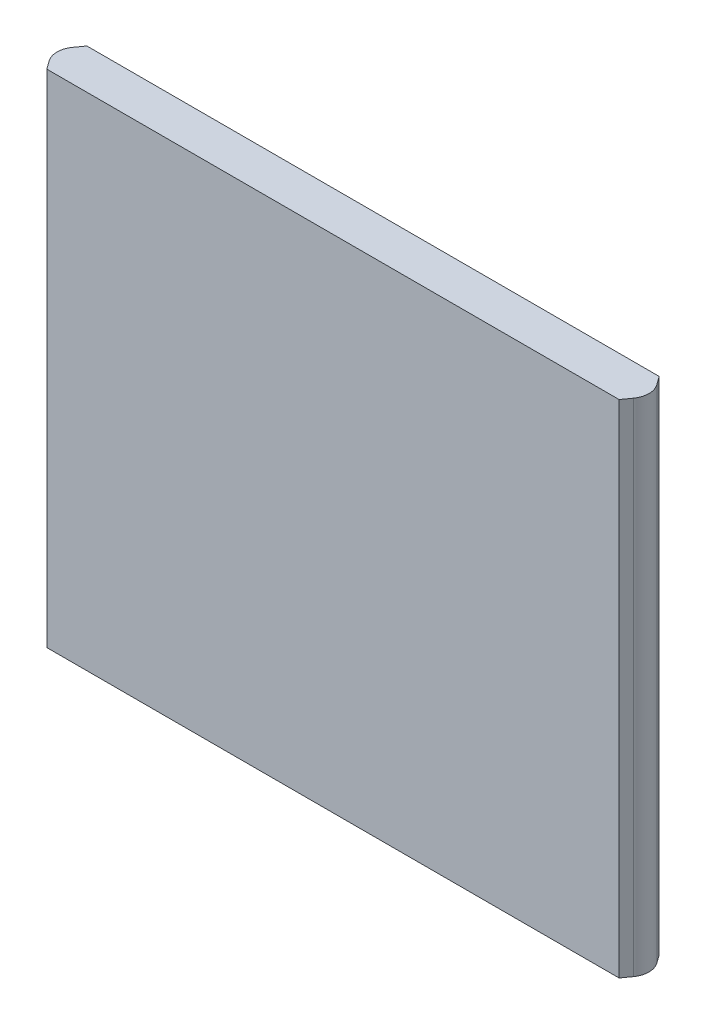
SolidWorks part; units mm, degrees
ref_plane "Front" through (0, 0, 0) normal (0, 0, 1) x (1, 0, 0)
ref_plane "Top" through (0, 0, 0) normal (0, 1, 0) x (1, 0, 0)
ref_plane "Right" through (0, 0, 0) normal (1, 0, 0) x (0, 0, -1)
sketch "草图1" plane through (0, 0, 0) normal (0, 0, 1) x (1, 0, 0)
  line L0 (0, 0) -> (0, -25)
  line L1 (0, -25) -> (30, -25)
  line L2 (30, -25) -> (30, 0)
  line L3 (30, 0) -> (0, 0)
extrude "凸台-拉伸1" add sketch "草图1" along normal blind 2
sketch "草图2" plane through (0, -25, 0) normal (0, -1, 0) x (1, 0, 0)
  line L0 (0.4228, 1.5855) -> (0.7222, 2)
  line L1 (0, 2) -> (0, 0) construction
  line L2 (0, 2) -> (30, 2) construction
  line L3 (0.4228, 0.4145) -> (0.7222, 0)
  line L4 (0, 0) -> (30, 0) construction
  line L5 (0.7222, 0) -> (0, 0)
  line L6 (0, 0) -> (0, 1)
  line L7 (0, 2) -> (0, 1)
  line L8 (0, 2) -> (0.7222, 2)
  line L9 (15, 2) -> (15, -4.0308) construction
  line L10 (30, 0) -> (30, 1)
  line L11 (29.2778, 0) -> (30, 0)
  line L12 (29.5772, 0.4145) -> (29.2778, 0)
  line L13 (29.5772, 1.5855) -> (29.2778, 2)
  line L14 (30, 2) -> (29.2778, 2)
  line L15 (30, 2) -> (30, 1)
  arc A0 (0.4228, 0.4145) -> (0.4228, 1.5855) centre (1.2335, 1) cw
  arc A1 (29.5772, 0.4145) -> (29.5772, 1.5855) centre (28.7665, 1) ccw
  dimension "D1" = 1
extrude "切除-拉伸1" cut sketch "草图2" against normal through all
sketch "草图3" plane through (0, -25, 0) normal (0, -1, 0) x (1, 0, 0)
  line L0 (15, 2) -> (15, 0)
  line L1 (0.7222, 2) -> (29.2778, 2) construction
  line L2 (0.7222, 0) -> (29.2778, 0) construction
  circle A0 centre (15, 1) radius 0.3
extrude "切除-拉伸2" cut sketch "草图3" against normal blind 3 contours L0 A0 | L0 A0
